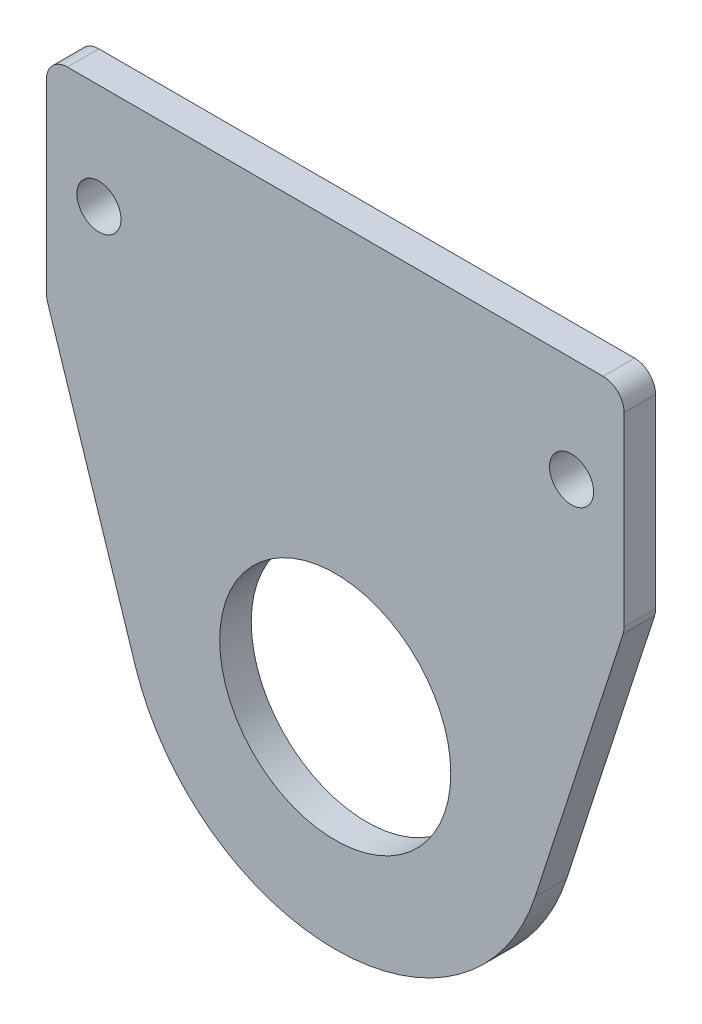
SolidWorks part; units mm, degrees
material "5052-H34"
ref_plane "正面" through (0, 0, 0) normal (0, 0, 1) x (1, 0, 0)
ref_plane "平面" through (0, 0, 0) normal (0, 1, 0) x (1, 0, 0)
ref_plane "右側面" through (0, 0, 0) normal (1, 0, 0) x (0, 0, -1)
sketch "ｽｹｯﾁ1" plane through (0, 0, 0) normal (0, 0, 1) x (1, 0, 0)
  line L0 (0, 10) -> (0, 0) construction
  line L1 (-27.5, 10) -> (27.5, 10)
  line L2 (-27.5, 10) -> (-27.5, -10)
  line L3 (-27.5, -10) -> (27.5, -10)
  line L4 (27.5, 10) -> (27.5, -10)
  line L5 (-27.5, 10) -> (27.5, -10) construction
  line L6 (-27.5, -10) -> (27.5, 10) construction
  line L7 (0, 0) -> (22.5, 0) construction
  line L8 (0, -30) -> (0, 0) construction
  line L9 (-27.5, -10) -> (-19.027, -36.1622)
  line L10 (27.5, -10) -> (19.027, -36.1622)
  circle A0 centre (22.5, 0) radius 2.1
  circle A1 centre (-22.5, 0) radius 2.1
  circle A2 centre (0, -30) radius 11
  circle A3 centre (0, -30) radius 20
  point P0 (0, 0)
  dimension "D3" = 4.2
  dimension "D5" = 22
  dimension "D7" = 40
  dimension "D1" = 20
  dimension "D2" = 55
  dimension "D4" = 45
  dimension "D6" = 30
extrude "ﾎﾞｽ - 押し出し1" add sketch "ｽｹｯﾁ1" along normal blind 3 contours L4 L1 L2 L3 A0 A1 | A3 L3 L9 | A3 A2 | A3 L10 L3
fillet "ﾌｨﾚｯﾄ1" radius 2 4 edges at (-27.5, -10, 1.5) (27.5, -10, 1.5) (27.5, 10, 1.5) (-27.5, 10, 1.5)
